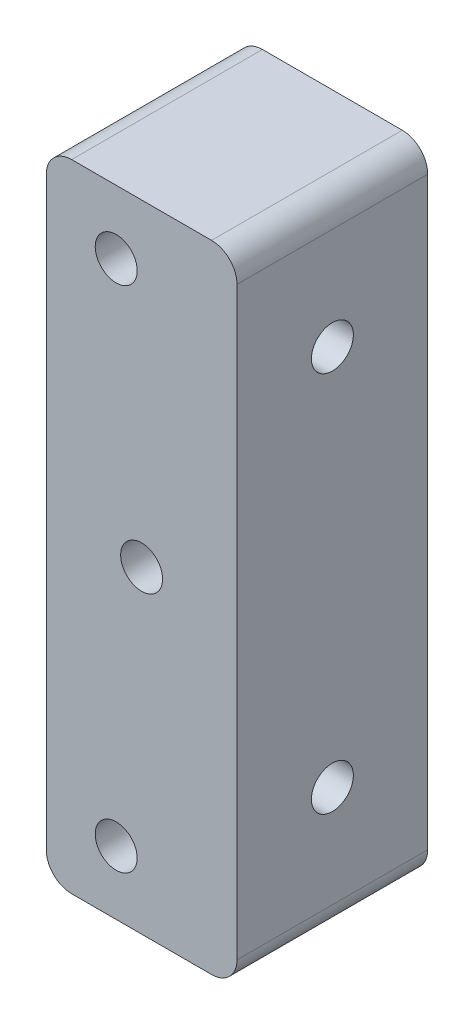
SolidWorks part; units mm, degrees
material "5052-H34"
ref_plane "正面" through (0, 0, 0) normal (0, 0, 1) x (1, 0, 0)
ref_plane "平面" through (0, 0, 0) normal (0, 1, 0) x (1, 0, 0)
ref_plane "右側面" through (0, 0, 0) normal (1, 0, 0) x (0, 0, -1)
sketch "ｽｹｯﾁ1" plane through (0, 0, 0) normal (0, 0, 1) x (1, 0, 0)
  line L0 (7.5, 50) -> (7.5, 0) construction
  line L1 (0, 0) -> (15, 0)
  line L2 (0, 0) -> (0, 50)
  line L3 (0, 50) -> (15, 50)
  line L4 (15, 0) -> (15, 50)
  line L5 (15, 25) -> (0, 25) construction
  circle A0 centre (5.5, 5) radius 1.65
  circle A1 centre (5.5, 45) radius 1.65
  circle A2 centre (7.5, 25) radius 1.65
  dimension "D3" = 3.3
  dimension "D4" = 5.5
  dimension "D5" = 5
  dimension "D6" = 3.3
  dimension "D1" = 15
  dimension "D2" = 50
extrude "ﾎﾞｽ - 押し出し1" add sketch "ｽｹｯﾁ1" along normal blind 15
sketch "ｽｹｯﾁ2" plane through (0, 0, 0) normal (-1, 0, 0) x (0, 0, 1)
  line L0 (7.5, 50) -> (7.5, 0) construction
  line L1 (15, 50) -> (0, 50) construction
  line L2 (15, 0) -> (0, 0) construction
  line L3 (15, 25) -> (0, 25) construction
  line L4 (15, 50) -> (15, 0) construction
  line L5 (0, 50) -> (0, 0) construction
  circle A0 centre (7.5, 40) radius 1.65
  circle A1 centre (7.5, 10) radius 1.65
  dimension "D1" = 3.3
  dimension "D2" = 30
extrude "ｶｯﾄ - 押し出し1" cut sketch "ｽｹｯﾁ2" against normal up to surface (15 mm away) up to face at (15, 25, 7.5)
fillet "ﾌｨﾚｯﾄ1" radius 2 4 edges at (15, 0, 7.5) (0, 0, 7.5) (15, 50, 7.5) (0, 50, 7.5)
